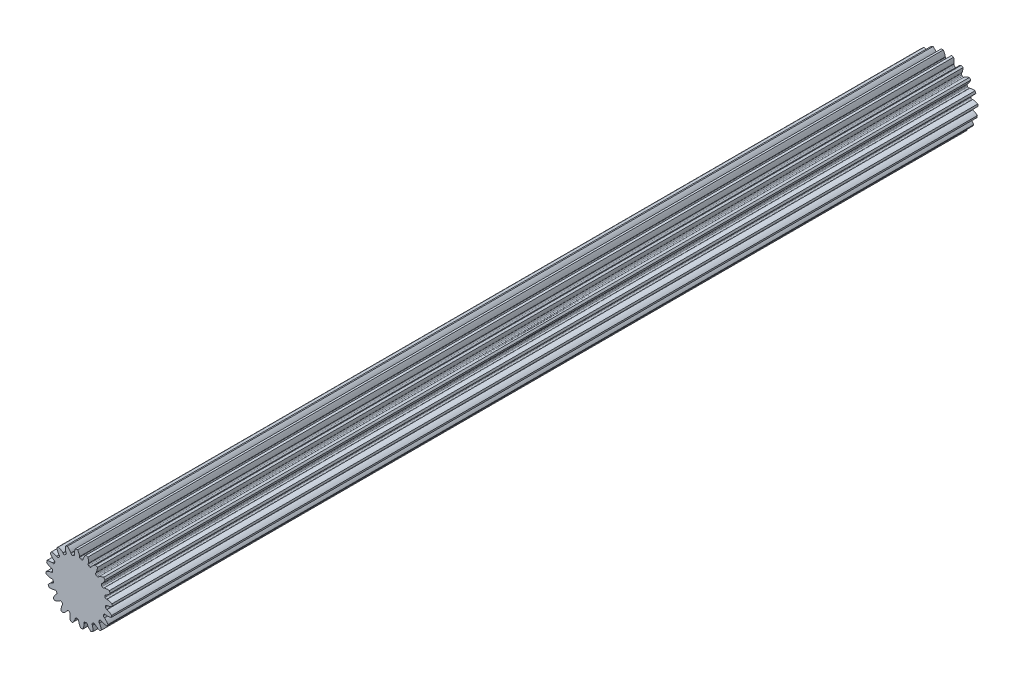
SolidWorks part; units mm, degrees
ref_plane "Front" through (0, 0, 0) normal (0, 0, 1) x (1, 0, 0)
ref_plane "Top" through (0, 0, 0) normal (0, 1, 0) x (1, 0, 0)
ref_plane "Right" through (0, 0, 0) normal (1, 0, 0) x (0, 0, -1)
sketch "Sketch1" plane through (0, 0, 0) normal (0, 0, 1) x (1, 0, 0)
  line L0 (-254, 0) -> (254, 0) construction
  circle A0 centre (0, 0) radius 11.684
  circle A1 centre (0, 0) radius 10.5791 construction
  circle A3 centre (0, 0) radius 9.3551 construction
  dimension "D1" = 1.224
  dimension "D2" = 2.3289
  dimension "D3" = 1.1049
extrude "Boss-Extrude1" add sketch "Sketch1" against normal blind 304.8
sketch "Sketch3" plane through (0, 0, 0) normal (0, 0, 1) x (1, 0, 0)
  line L0 (0, 0) -> (0, 11.684) construction
  line L1 (-3.4001, 9.3416) -> (0, 10.5791)
  line L2 (-9.5921, 10.5791) -> (9.5921, 10.5791) construction
  line L3 (-9.0136, 7.2984) -> (9.0136, 13.8598) construction
  line L4 (-3.4001, 9.3416) -> (0, 0) construction
  line L5 (-7.1592, 6.8972) -> (0, 0) construction
  line L6 (-7.1592, 6.8972) -> (-1.5108, 12.7601) construction
  line L7 (-2.3618, 9.6565) -> (0, 0) construction
  line L8 (-2.3618, 9.6565) -> (0.0984, 10.2582) construction
  arc A0 (-3.4001, 9.3416) -> (-7.1592, 6.8972) centre (0, 0) ccw
  circle A1 centre (0, 0) radius 10.5791 construction
  circle A2 centre (0, 0) radius 9.9411 construction
  arc A3 (-3.4001, 9.3416) -> (-2.3618, 9.6565) centre (0, 0) cw
  circle A4 centre (0, 0) radius 11.684 construction
  point P6 (0, 10.5791)
  dimension "D1" = 3.6183
  dimension "D3" = 8.1411
  dimension "D5" = 2.5328
  dimension "D2" = 4.5228
  dimension "D4" = 1.0855
sketch "Sketch4" plane through (0, 0, 0) normal (0, 0, 1) x (1, 0, 0)
  line L0 (0, 0) -> (0.8275, 10.514) construction
  line L1 (0.1728, 9.9396) -> (0.1728, 9.3535)
  line L2 (0, 10.5791) -> (1.6549, 10.4489) construction
  line L3 (1.3842, 9.8443) -> (1.2925, 9.2654)
  line L4 (0.1728, 9.3535) -> (0, 0) construction
  line L5 (0, 0) -> (0, 11.684) construction
  line L6 (-7.1592, 6.8972) -> (-1.5108, 12.7601) construction
  line L7 (-7.1592, 6.8972) -> (-1.5108, 12.7601) construction
  arc A0 (1.2925, 9.2654) -> (0.1728, 9.3535) centre (0, 0) ccw
  arc A1 (0, 10.5791) -> (1.6549, 10.4489) centre (0, 0) cw construction
  circle A2 centre (0, 0) radius 10.5791 construction
  circle A3 centre (0, 0) radius 9.9411 construction
  circle A4 centre (0, 0) radius 9.3551 construction
  arc A5 (3.4883, 12.3667) -> (-1.5108, 12.7601) centre (0, 0) ccw
  spline S0 degree 2 poles (-1.5108, 12.7601) (-0.1511, 11.5691) (0.1728, 9.9396) knots 0 0 0 1 1 1
  spline S1 degree 2 poles (3.4883, 12.3667) (1.9591, 11.403) (1.3842, 9.8443) knots 0 0 0 1 1 1
  dimension "D1" = 1.6618
extrude "Cut-Extrude1" cut sketch "Sketch4" against normal through all
fillet "Fillet1" radius 0.4154 2 edges at (1.2925, 9.2654, -152.4) (0.1728, 9.3535, -152.4)
pattern_circular "CirPattern1" count 20 over 360 about axis through (0, 0, -304.8) along (0, 0, 1) of "Cut-Extrude1", "Fillet1"
sketch "Pitch Dia" plane through (0, 0, 0) normal (0, 0, 1) x (1, 0, 0)
  circle A0 centre (0, 0) radius 10.5791 construction
  circle A1 centre (0, 0) radius 10.5791
equation "\"D2@Sketch3\" = \"D1@Sketch3\"*1.25"
equation "\"D3@Sketch3\" = \"D1@Sketch3\"+\"D2@Sketch3\""
equation "\"D4@Sketch3\" = \"D1@Sketch3\"*.3"
equation "\"D5@Sketch3\" = \"D1@Sketch3\"-\"D4@Sketch3\""
equation "\"D1@Sketch4\" = 1.5708/(\"Number of Teeth@Sketch1\"/\"Pitch Diameter@Sketch1\")"
equation "\"D1@CirPattern1\" = \"Number of Teeth@Sketch1\""
equation "\"D1@Fillet1\" = \"D1@Sketch4\"*.25"
equation "\"D1@Sketch1\" = 1.157/(\"Number of Teeth@Sketch1\"/\"Pitch Diameter@Sketch1\")"
